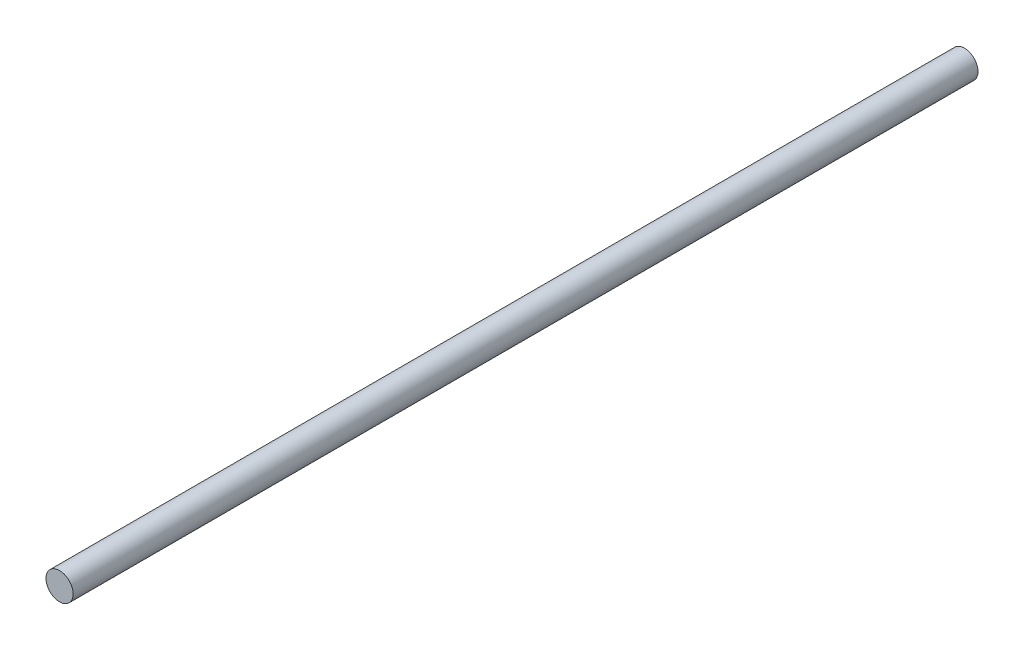
SolidWorks part; units mm, degrees
material "AISI 304"
ref_plane "Front Plane" through (0, 0, 0) normal (0, 0, 1) x (1, 0, 0)
ref_plane "Top Plane" through (0, 0, 0) normal (0, 1, 0) x (1, 0, 0)
ref_plane "Right Plane" through (0, 0, 0) normal (1, 0, 0) x (0, 0, -1)
sketch "Sketch2" plane through (0, 0, 0) normal (0, 0, 1) x (1, 0, 0)
  circle A0 centre (0, 0) radius 1.5
  dimension "D1" = 3
extrude "Boss-Extrude1" add sketch "Sketch2" along normal blind 100
